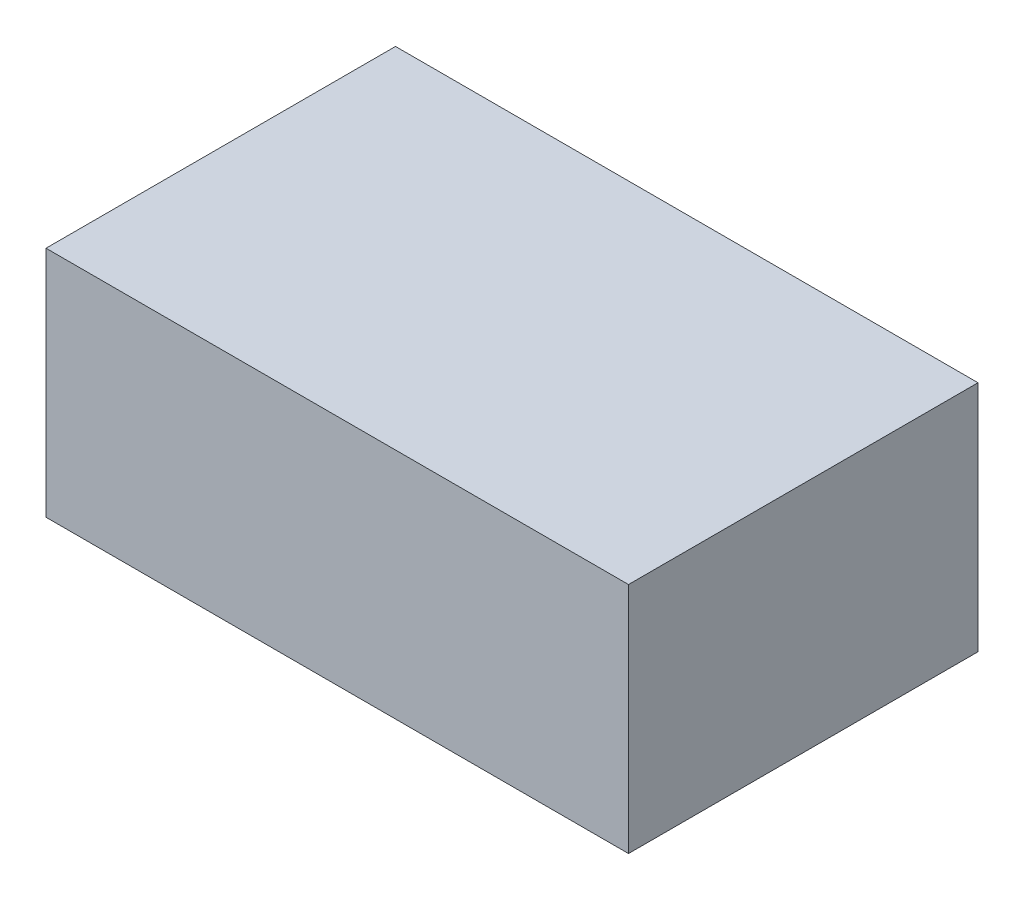
SolidWorks part; units mm, degrees
ref_plane "Plan de face" through (0, 0, 0) normal (0, 0, 1) x (1, 0, 0)
ref_plane "Plan de dessus" through (0, 0, 0) normal (0, 1, 0) x (1, 0, 0)
ref_plane "Plan de droite" through (0, 0, 0) normal (1, 0, 0) x (0, 0, -1)
sketch "Esquisse1" plane through (0, 0, 0) normal (0, 1, 0) x (1, 0, 0)
  line L0 (-55, 0) -> (55, 0) construction
  line L1 (-125, 75) -> (125, 75)
  line L2 (-125, 75) -> (-125, -75)
  line L3 (-125, -75) -> (125, -75)
  line L4 (125, 75) -> (125, -75)
  line L5 (0, -55) -> (0, 55) construction
  dimension "D1" = 150
  dimension "D2" = 250
  dimension "D3" = 75
  dimension "D4" = 125
extrude "Boss.-Extru.1" add sketch "Esquisse1" along normal blind 100
sketch "Esquisse2" plane through (0, 100, 0) normal (0, 1, 0) x (1, 0, 0)
  line L0 (125, 75) -> (-125, 75) construction
  line L2 (125, -75) -> (125, 75) construction
  circle A0 centre (50, 0) radius 70
  dimension "D3" = 140
  dimension "D1" = 75
  dimension "D2" = 75
